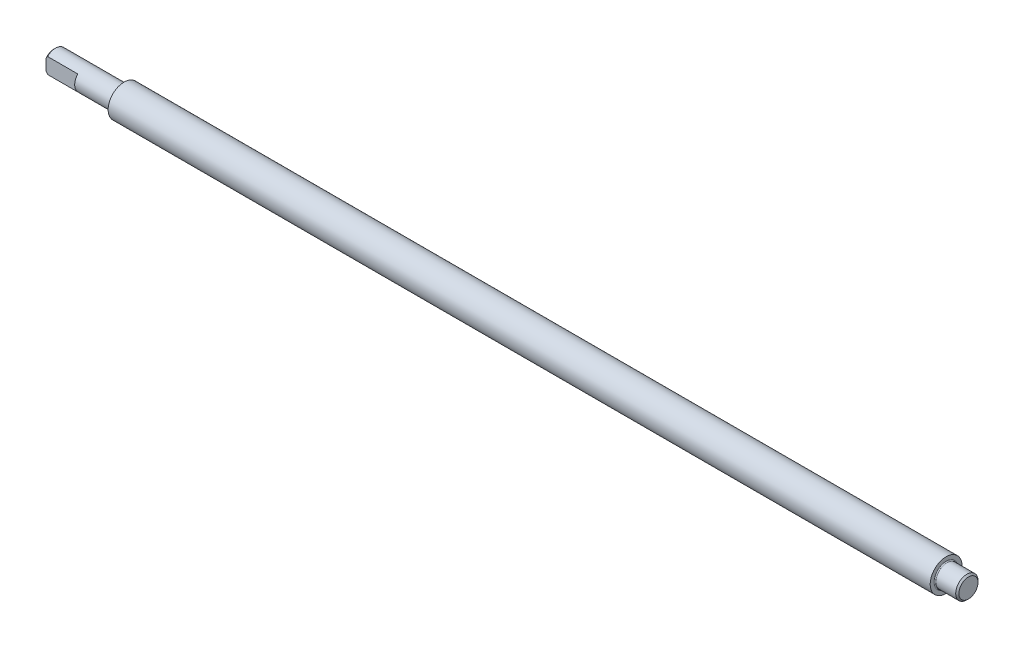
SolidWorks part; units mm, degrees
ref_plane "Front Plane" through (0, 0, 0) normal (0, 0, 1) x (1, 0, 0)
ref_plane "Top Plane" through (0, 0, 0) normal (0, 1, 0) x (1, 0, 0)
ref_plane "Right Plane" through (0, 0, 0) normal (1, 0, 0) x (0, 0, -1)
sketch "Sketch1" plane through (0, 0, 0) normal (0, 0, 1) x (1, 0, 0)
  line L0 (22, 5) -> (22, 0)
  line L1 (22, 0) -> (280, 0)
  line L2 (280, 0) -> (280, 5)
  line L3 (280, 5) -> (22, 5)
  line L4 (22, 0) -> (280, 0) construction
  dimension "D1" = 258
  dimension "D2" = 5
revolve "Revolve1" add sketch "Sketch1" angle 360 about L4
sketch "Sketch2" plane through (22, 0, 0) normal (-1, 0, 0) x (0, 0, 1)
  circle A0 centre (0, 0) radius 3.5
  dimension "D1" = 7
extrude "Boss-Extrude1" add sketch "Sketch2" along normal blind 22
sketch "Sketch3" plane through (0, 0, 0) normal (-1, 0, 0) x (0, 0, 1)
  line L0 (2.5, 2.4495) -> (2.5, -2.4495)
  arc A0 (2.5, -2.4495) -> (2.5, 2.4495) centre (0, 0) ccw
  circle A1 centre (0, 0) radius 3.5 construction
  dimension "D1" = 3.5
  dimension "D2" = 2.5
  dimension "D3" = 2.4495
  dimension "D4" = 2.4495
extrude "Cut-Extrude1" cut sketch "Sketch3" against normal blind 10
sketch "Sketch4" plane through (280, 0, 0) normal (1, 0, 0) x (0, 0, -1)
  circle A0 centre (0, 0) radius 3.5
  dimension "D1" = 7
extrude "Boss-Extrude2" add sketch "Sketch4" along normal blind 7
chamfer "Chamfer1" distance 0.5 angle 45 2 edges at (287, 0, -3.5) (0, 0, -3.5)
fillet "Fillet1" radius 0.3 2 edges at (22, 0, 3.5) (280, 0, -3.5)
